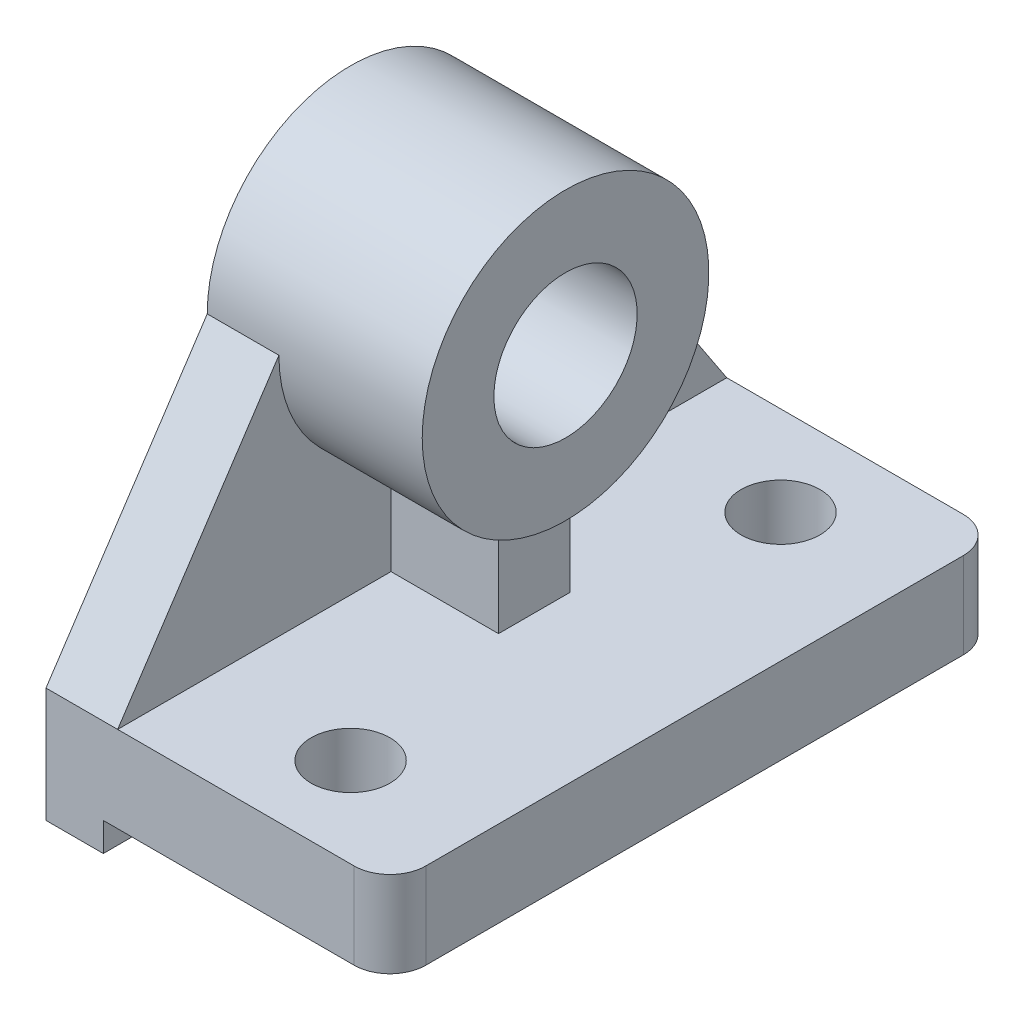
SolidWorks part; units mm, degrees
ref_plane "Front Plane" through (0, 0, 0) normal (0, 0, 1) x (1, 0, 0)
ref_plane "Top Plane" through (0, 0, 0) normal (0, 1, 0) x (1, 0, 0)
ref_plane "Right Plane" through (0, 0, 0) normal (1, 0, 0) x (0, 0, -1)
sketch "Sketch2" plane through (0, 0, 0) normal (0, 1, 0) x (1, 0, 0)
  line L0 (-18.7654, -74.5802) -> (-18.7654, 10.4198)
  line L1 (-18.7654, 10.4198) -> (24.2346, 10.4198)
  line L2 (29.2346, 5.4198) -> (29.2346, -69.5802)
  line L3 (24.2346, -74.5802) -> (-18.7654, -74.5802)
  arc A0 (29.2346, -69.5802) -> (24.2346, -74.5802) centre (24.2346, -69.5802) cw
  arc A1 (29.2346, 5.4198) -> (24.2346, 10.4198) centre (24.2346, 5.4198) ccw
  point P6 (29.2346, -74.5802)
  point P9 (29.2346, 10.4198)
  dimension "D3" = 5
  dimension "D1" = 48
  dimension "D2" = 85
extrude "Boss-Extrude1" add sketch "Sketch2" against normal blind 12
sketch "Sketch3" plane through (-18.7654, 0, 0) normal (-1, 0, 0) x (0, 0, 1)
  circle A0 centre (32.0802, 33.9659) radius 20
  circle A1 centre (32.0802, 33.9659) radius 10
  dimension "D1" = 40
  dimension "D2" = 20
extrude "Boss-Extrude2" add sketch "Sketch3" against normal blind 30 separate body
sketch "Sketch4" plane through (-18.7654, 0, 0) normal (-1, 0, 0) x (0, 0, 1)
  line L0 (12.0802, 33.9659) -> (-10.4198, 0)
  line L1 (-10.4198, 0) -> (74.5802, 0)
  line L2 (74.5802, 0) -> (52.0802, 33.9659)
  circle A0 centre (32.0802, 33.9659) radius 20 construction
  arc A1 (12.0802, 33.9659) -> (52.0802, 33.9659) centre (32.0802, 33.9659) ccw
extrude "Boss-Extrude3" add sketch "Sketch4" against normal blind 10
sketch "Sketch5" plane through (0, 0, 0) normal (0, 1, 0) x (1, 0, 0)
  line L0 (29.2346, -69.5802) -> (29.2346, 5.4198) construction
  line L1 (24.2346, 10.4198) -> (-8.7654, 10.4198) construction
  line L2 (-8.7654, -74.5802) -> (24.2346, -74.5802) construction
  circle A0 centre (11.2346, -2.0802) radius 5.5
  circle A1 centre (11.2346, -62.0802) radius 5.5
  dimension "D1" = 11
  dimension "D2" = 11
  dimension "D3" = 18
  dimension "D4" = 12.5
  dimension "D5" = 12.5
  dimension "D6" = 18
extrude "Cut-Extrude1" cut sketch "Sketch5" against normal through all
sketch "Sketch6" plane through (0, 0, 74.5802) normal (0, 0, 1) x (1, 0, 0)
  line L0 (-18.7654, -12) -> (-18.7654, -16)
  line L1 (-18.7654, -16) -> (-10.7654, -16)
  line L2 (-10.7654, -16) -> (-10.7654, -12)
  line L3 (-18.7654, -12) -> (24.2346, -12) construction
  line L4 (-10.7654, -12) -> (-18.7654, -12)
  dimension "D1" = 8
  dimension "D2" = 4
extrude "Boss-Extrude4" add sketch "Sketch6" against normal blind 85
ref_plane "Plane1" through (-8.7654, 0, 0) normal (-1, 0, 0) x (0, 0, 1)
sketch "Sketch7" plane through (-8.7654, 0, 0) normal (-1, 0, 0) x (0, 0, 1)
  line L0 (31.4363, 20.4319) -> (31.4363, 0)
  line L2 (36.4363, 14.2068) -> (36.4363, 0)
  line L3 (36.4363, 0) -> (26.4363, 0)
  line L4 (26.4363, 0) -> (26.4363, 20.4319)
  line L5 (26.4363, 20.4319) -> (36.4363, 20.4319)
  line L6 (36.4363, 20.4319) -> (36.4363, 14.2068)
  dimension "D1" = 5
extrude "Boss-Extrude5" add sketch "Sketch7" against normal blind 15 contours L6 L5 L0 L3 L2 | L5 L4 L3 L0
